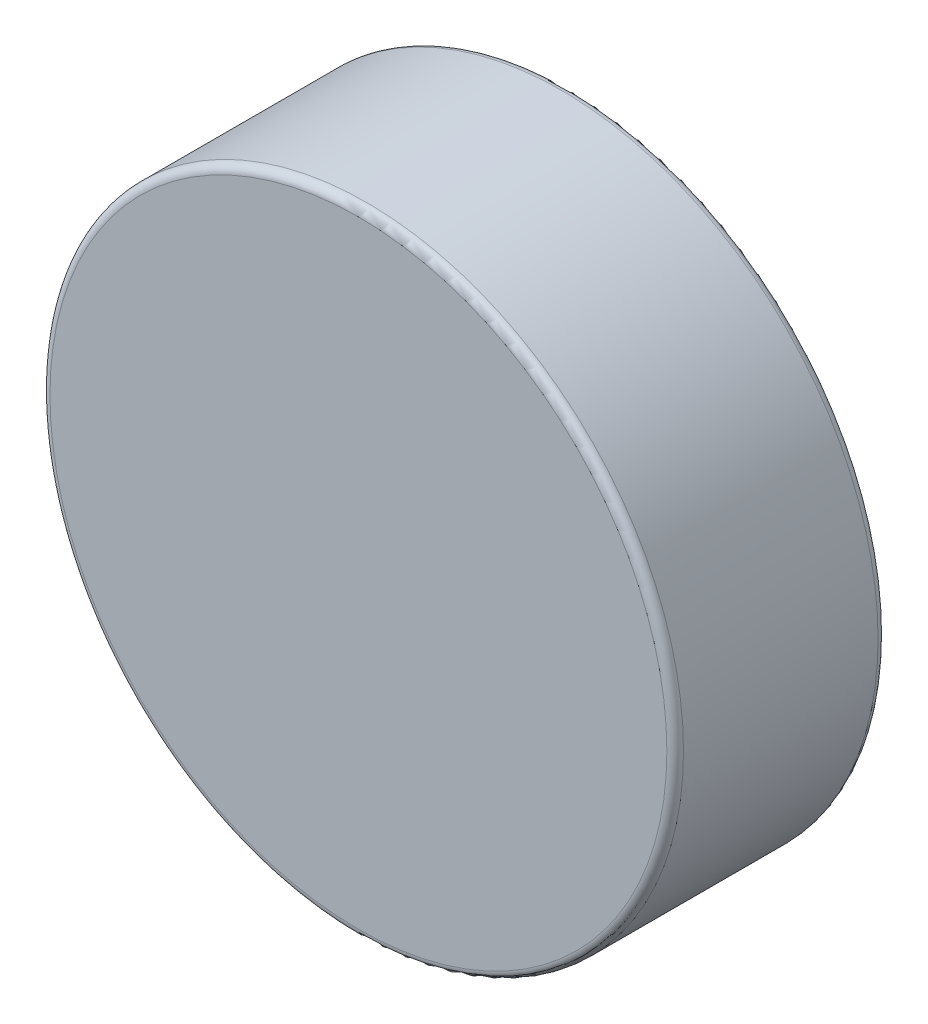
SolidWorks part; units mm, degrees
ref_plane "Front" through (0, 0, 0) normal (0, 0, 1) x (1, 0, 0)
ref_plane "Top" through (0, 0, 0) normal (0, 1, 0) x (1, 0, 0)
ref_plane "Right" through (0, 0, 0) normal (1, 0, 0) x (0, 0, -1)
sketch "Esquisse1" plane through (0, 0, 0) normal (0, 0, 1) x (1, 0, 0)
  circle A0 centre (0, 0) radius 38.1
  dimension "D1" = 76.2
extrude "Boss.-Extru.1" add sketch "Esquisse1" along normal blind 25.4
fillet "Congé1" radius 1 2 edges at (38.1, 0, 25.4) (38.1, 0, 0)
